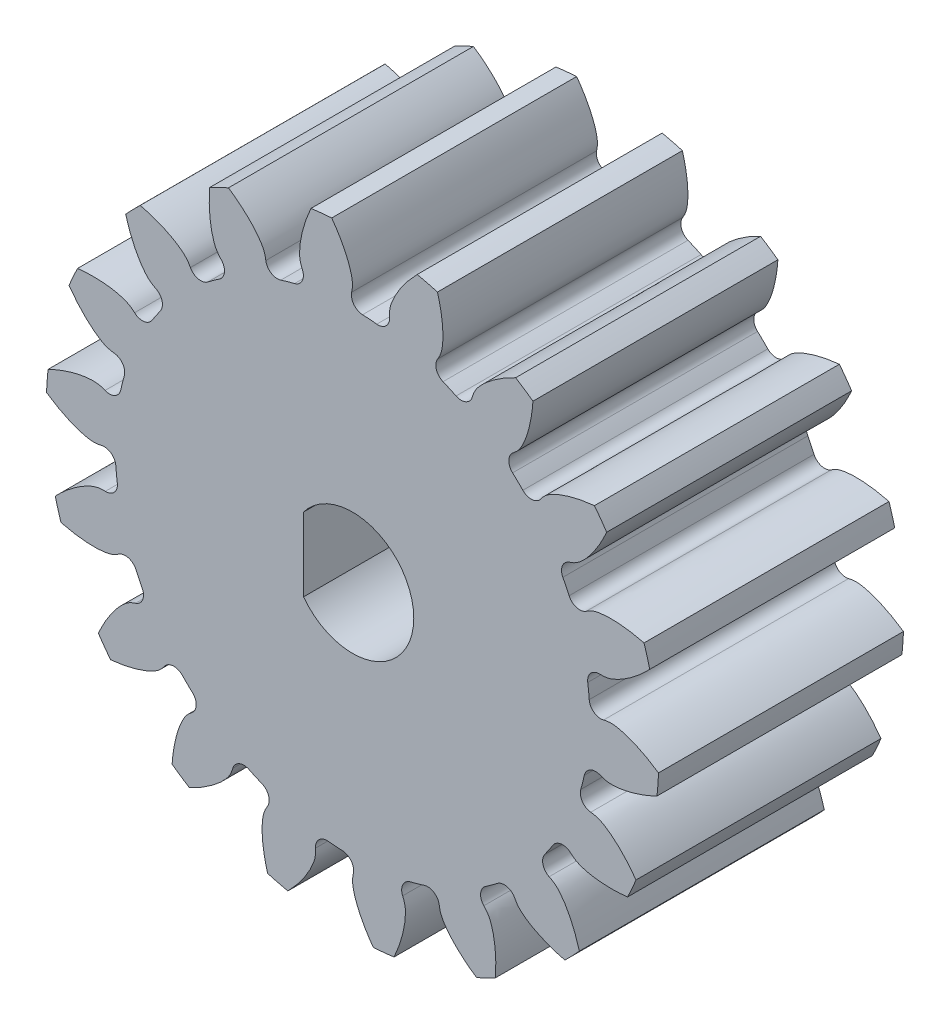
SolidWorks part; units mm, degrees
ref_plane "前视基准面" through (0, 0, 0) normal (0, 0, 1) x (1, 0, 0)
ref_plane "上视基准面" through (0, 0, 0) normal (0, 1, 0) x (1, 0, 0)
ref_plane "右视基准面" through (0, 0, 0) normal (1, 0, 0) x (0, 0, -1)
sketch "草图1" plane through (0, 0, 0) normal (0, 0, 1) x (1, 0, 0)
  line L0 (-0.8, -0.6) -> (-0.8, 0.6)
  arc A0 (-0.8, 0.6) -> (-0.8, -0.6) centre (0, 0) cw
  arc A1 (4.15, 2.7888) -> (3.9504, 3.065) centre (0, 0) ccw
  arc A2 (3.0713, 2.7184) -> (2.7814, 2.698) centre (2.9178, 2.8303) cw
  arc A3 (2.7814, 2.698) -> (2.614, 2.8606) centre (0, 0) ccw
  arc A4 (2.614, 2.8606) -> (2.6257, 3.151) centre (2.7421, 3.0008) cw
  arc A5 (2.9459, 4.04) -> (2.6639, 4.2313) centre (0, 0) ccw
  arc A6 (1.9563, 3.6049) -> (1.6909, 3.4866) centre (1.7738, 3.6576) cw
  arc A7 (1.6909, 3.4866) -> (1.4779, 3.5821) centre (0, 0) ccw
  arc A8 (1.4779, 3.5821) -> (1.3896, 3.859) centre (1.5504, 3.7577) cw
  arc A9 (1.3865, 4.8039) -> (1.0561, 4.8872) centre (0, 0) ccw
  arc A10 (0.6054, 4.0566) -> (0.3964, 3.8547) centre (0.4159, 4.0437) cw
  arc A11 (0.3964, 3.8547) -> (0.1637, 3.8715) centre (0, 0) ccw
  arc A12 (0.1637, 3.8715) -> (-0.014, 4.1015) centre (0.1717, 4.0614) cw
  arc A13 (-0.3402, 4.9884) -> (-0.6792, 4.9537) centre (0, 0) ccw
  arc A14 (-0.8185, 4.019) -> (-0.9459, 3.7578) centre (-0.9922, 3.942) cw
  arc A15 (-0.9459, 3.7578) -> (-1.1703, 3.694) centre (0, 0) ccw
  arc A16 (-1.1703, 3.694) -> (-1.416, 3.8494) centre (-1.2277, 3.8752) cw
  arc A17 (-2.0258, 4.5712) -> (-2.3324, 4.4226) centre (0, 0) ccw
  arc A18 (-2.1438, 3.4967) -> (-2.1741, 3.2077) centre (-2.2807, 3.3649) cw
  arc A19 (-2.1741, 3.2077) -> (-2.3632, 3.071) centre (0, 0) ccw
  arc A20 (-2.3632, 3.071) -> (-2.6471, 3.1329) centre (-2.4791, 3.2216) cw
  arc A21 (-3.4671, 3.6027) -> (-3.7044, 3.3582) centre (0, 0) ccw
  arc A22 (-3.2104, 2.5526) -> (-3.14, 2.2706) centre (-3.294, 2.382) cw
  arc A23 (-3.14, 2.2706) -> (-3.271, 2.0775) centre (0, 0) ccw
  arc A24 (-3.271, 2.0775) -> (-3.559, 2.0386) centre (-3.4314, 2.1794) cw
  arc A25 (-4.4902, 2.1996) -> (-4.6296, 1.8887) centre (0, 0) ccw
  arc A26 (-3.8899, 1.3006) -> (-3.7273, 1.0597) centre (-3.91, 1.1117) cw
  arc A27 (-3.7273, 1.0597) -> (-3.7843, 0.8335) centre (0, 0) ccw
  arc A28 (-3.7843, 0.8335) -> (-4.0416, 0.6984) centre (-3.9699, 0.8743) cw
  arc A29 (-4.9717, 0.5312) -> (-4.9963, 0.1914) centre (0, 0) ccw
  arc A30 (-4.1001, -0.1082) -> (-3.8649, -0.279) centre (-4.0545, -0.2926) cw
  arc A31 (-3.8649, -0.279) -> (-3.8411, -0.5111) centre (0, 0) ccw
  arc A32 (-3.8411, -0.5111) -> (-4.0368, -0.726) centre (-4.0295, -0.5362) cw
  arc A33 (-4.8536, -1.2012) -> (-4.7605, -1.529) centre (0, 0) ccw
  arc A34 (-3.8158, -1.504) -> (-3.5364, -1.584) centre (-3.7098, -1.6617) cw
  arc A35 (-3.5364, -1.584) -> (-3.4347, -1.794) centre (0, 0) ccw
  arc A36 (-3.4347, -1.794) -> (-3.545, -2.0629) centre (-3.6031, -1.882) cw
  arc A37 (-4.15, -2.7888) -> (-3.9504, -3.065) centre (0, 0) ccw
  arc A38 (-3.0713, -2.7184) -> (-2.7814, -2.698) centre (-2.9178, -2.8303) cw
  arc A39 (-2.7814, -2.698) -> (-2.614, -2.8606) centre (0, 0) ccw
  arc A40 (-2.614, -2.8606) -> (-2.6257, -3.151) centre (-2.7421, -3.0008) cw
  arc A41 (-2.9459, -4.04) -> (-2.6639, -4.2313) centre (0, 0) ccw
  arc A42 (-1.9563, -3.6049) -> (-1.6909, -3.4866) centre (-1.7738, -3.6576) cw
  arc A43 (-1.6909, -3.4866) -> (-1.4779, -3.5821) centre (0, 0) ccw
  arc A44 (-1.4779, -3.5821) -> (-1.3896, -3.859) centre (-1.5504, -3.7577) cw
  arc A45 (-1.3865, -4.8039) -> (-1.0561, -4.8872) centre (0, 0) ccw
  arc A46 (-0.6054, -4.0566) -> (-0.3964, -3.8547) centre (-0.4159, -4.0437) cw
  arc A47 (-0.3964, -3.8547) -> (-0.1637, -3.8715) centre (0, 0) ccw
  arc A48 (-0.1637, -3.8715) -> (0.014, -4.1015) centre (-0.1717, -4.0614) cw
  arc A49 (0.3402, -4.9884) -> (0.6792, -4.9537) centre (0, 0) ccw
  arc A50 (0.8185, -4.019) -> (0.9459, -3.7578) centre (0.9922, -3.942) cw
  arc A51 (0.9459, -3.7578) -> (1.1703, -3.694) centre (0, 0) ccw
  arc A52 (1.1703, -3.694) -> (1.416, -3.8494) centre (1.2277, -3.8752) cw
  arc A53 (2.0258, -4.5712) -> (2.3324, -4.4226) centre (0, 0) ccw
  arc A54 (2.1438, -3.4967) -> (2.1741, -3.2077) centre (2.2807, -3.3649) cw
  arc A55 (2.1741, -3.2077) -> (2.3632, -3.071) centre (0, 0) ccw
  arc A56 (2.3632, -3.071) -> (2.6471, -3.1329) centre (2.4791, -3.2216) cw
  arc A57 (3.4671, -3.6027) -> (3.7044, -3.3582) centre (0, 0) ccw
  arc A58 (3.2104, -2.5526) -> (3.14, -2.2706) centre (3.294, -2.382) cw
  arc A59 (3.14, -2.2706) -> (3.271, -2.0775) centre (0, 0) ccw
  arc A60 (3.271, -2.0775) -> (3.559, -2.0386) centre (3.4314, -2.1794) cw
  arc A61 (4.4902, -2.1996) -> (4.6296, -1.8887) centre (0, 0) ccw
  arc A62 (3.8899, -1.3006) -> (3.7273, -1.0597) centre (3.91, -1.1117) cw
  arc A63 (3.7273, -1.0597) -> (3.7843, -0.8335) centre (0, 0) ccw
  arc A64 (3.7843, -0.8335) -> (4.0416, -0.6984) centre (3.9699, -0.8743) cw
  arc A65 (4.9717, -0.5312) -> (4.9963, -0.1914) centre (0, 0) ccw
  arc A66 (4.1001, 0.1082) -> (3.8649, 0.279) centre (4.0545, 0.2926) cw
  arc A67 (3.8649, 0.279) -> (3.8411, 0.5111) centre (0, 0) ccw
  arc A68 (3.8411, 0.5111) -> (4.0368, 0.726) centre (4.0295, 0.5362) cw
  arc A69 (4.8536, 1.2012) -> (4.7605, 1.529) centre (0, 0) ccw
  arc A70 (3.8158, 1.504) -> (3.5364, 1.584) centre (3.7098, 1.6617) cw
  arc A71 (3.5364, 1.584) -> (3.4347, 1.794) centre (0, 0) ccw
  arc A72 (3.4347, 1.794) -> (3.545, 2.0629) centre (3.6031, 1.882) cw
  spline S0 degree 3 poles (4.15, 2.7888) (4.1194, 2.7195) (4.0858, 2.6514) (4.0489, 2.5852) (4.012, 2.5189) (3.9718, 2.4544) (3.9277, 2.3927) (3.8749, 2.3186) (3.8166, 2.2476) (3.7503, 2.1853) (3.706, 2.1437) (3.6558, 2.1059) (3.5996, 2.0827) (3.5817, 2.0753) (3.5635, 2.0688) (3.545, 2.0629) knots 0 0 0 0 0.000227 0.000227 0.000227 0.000455 0.000455 0.000455 0.000728 0.000728 0.000728 0.000912 0.000912 0.000912 0.00097 0.00097 0.00097 0.00097
  spline S1 degree 3 poles (3.0713, 2.7184) (3.1059, 2.7659) (3.1474, 2.8104) (3.1968, 2.8423) (3.3114, 2.9164) (3.4434, 2.9634) (3.5753, 2.9987) (3.698, 3.0314) (3.8241, 3.0527) (3.9504, 3.065) knots 0 0 0 0 0.000176 0.000176 0.000176 0.000584 0.000584 0.000584 0.000961 0.000961 0.000961 0.000961
  spline S2 degree 3 poles (2.9459, 4.04) (2.9408, 3.9644) (2.9325, 3.8889) (2.9205, 3.8141) (2.9085, 3.7392) (2.8928, 3.6648) (2.8725, 3.5917) (2.8482, 3.5041) (2.8177, 3.4174) (2.7767, 3.3362) (2.7493, 3.2819) (2.7151, 3.2292) (2.6702, 3.1882) (2.6559, 3.1752) (2.641, 3.1628) (2.6257, 3.151) knots 0 0 0 0 0.000227 0.000227 0.000227 0.000455 0.000455 0.000455 0.000728 0.000728 0.000728 0.000912 0.000912 0.000912 0.00097 0.00097 0.00097 0.00097
  spline S3 degree 3 poles (1.9563, 3.6049) (1.9726, 3.6614) (1.9964, 3.7174) (2.0319, 3.7642) (2.1142, 3.8731) (2.2222, 3.9624) (2.3341, 4.0407) (2.4382, 4.1134) (2.5494, 4.1765) (2.6639, 4.2313) knots 0 0 0 0 0.000176 0.000176 0.000176 0.000584 0.000584 0.000584 0.000961 0.000961 0.000961 0.000961
  spline S4 degree 3 poles (1.3865, 4.8039) (1.4076, 4.7311) (1.4256, 4.6573) (1.4399, 4.5829) (1.4542, 4.5085) (1.4649, 4.4332) (1.4708, 4.3576) (1.478, 4.2669) (1.479, 4.175) (1.4682, 4.0847) (1.461, 4.0243) (1.4469, 3.9631) (1.4188, 3.9092) (1.4098, 3.8921) (1.4, 3.8754) (1.3896, 3.859) knots 0 0 0 0 0.000227 0.000227 0.000227 0.000455 0.000455 0.000455 0.000728 0.000728 0.000728 0.000912 0.000912 0.000912 0.00097 0.00097 0.00097 0.00097
  spline S5 degree 3 poles (0.6054, 4.0566) (0.6014, 4.1153) (0.6046, 4.176) (0.6219, 4.2322) (0.6621, 4.3627) (0.733, 4.4835) (0.8114, 4.5953) (0.8843, 4.6992) (0.9672, 4.7965) (1.0561, 4.8872) knots 0 0 0 0 0.000176 0.000176 0.000176 0.000584 0.000584 0.000584 0.000961 0.000961 0.000961 0.000961
  spline S6 degree 3 poles (-0.3402, 4.9884) (-0.2955, 4.9272) (-0.2533, 4.8641) (-0.2144, 4.799) (-0.1755, 4.7339) (-0.1397, 4.6668) (-0.1082, 4.5978) (-0.0705, 4.515) (-0.0382, 4.4291) (-0.0174, 4.3405) (-0.0035, 4.2813) (0.0041, 4.219) (-0.0038, 4.1587) (-0.0064, 4.1395) (-0.0099, 4.1205) (-0.014, 4.1015) knots 0 0 0 0 0.000227 0.000227 0.000227 0.000455 0.000455 0.000455 0.000728 0.000728 0.000728 0.000912 0.000912 0.000912 0.00097 0.00097 0.00097 0.00097
  spline S7 degree 3 poles (-0.8185, 4.019) (-0.8424, 4.0728) (-0.8601, 4.1309) (-0.8631, 4.1896) (-0.87, 4.326) (-0.8447, 4.4638) (-0.8093, 4.5957) (-0.7763, 4.7183) (-0.7317, 4.8381) (-0.6792, 4.9537) knots 0 0 0 0 0.000176 0.000176 0.000176 0.000584 0.000584 0.000584 0.000961 0.000961 0.000961 0.000961
  spline S8 degree 3 poles (-2.0258, 4.5712) (-1.9628, 4.529) (-1.9016, 4.4841) (-1.8428, 4.4363) (-1.784, 4.3884) (-1.7274, 4.3376) (-1.6743, 4.2835) (-1.6105, 4.2186) (-1.5507, 4.1489) (-1.5009, 4.0728) (-1.4676, 4.022) (-1.4391, 3.9659) (-1.426, 3.9066) (-1.4218, 3.8877) (-1.4186, 3.8686) (-1.416, 3.8494) knots 0 0 0 0 0.000227 0.000227 0.000227 0.000455 0.000455 0.000455 0.000728 0.000728 0.000728 0.000912 0.000912 0.000912 0.00097 0.00097 0.00097 0.00097
  spline S9 degree 3 poles (-2.1438, 3.4967) (-2.1845, 3.539) (-2.2211, 3.5876) (-2.244, 3.6418) (-2.2971, 3.7675) (-2.3205, 3.9057) (-2.3323, 4.0417) (-2.3432, 4.1682) (-2.3423, 4.296) (-2.3324, 4.4226) knots 0 0 0 0 0.000176 0.000176 0.000176 0.000584 0.000584 0.000584 0.000961 0.000961 0.000961 0.000961
  spline S10 degree 3 poles (-3.4671, 3.6027) (-3.3935, 3.5845) (-3.3206, 3.5633) (-3.249, 3.5385) (-3.1773, 3.5136) (-3.1068, 3.4852) (-3.0383, 3.4526) (-2.9562, 3.4134) (-2.8762, 3.3683) (-2.8033, 3.3138) (-2.7547, 3.2775) (-2.7087, 3.2346) (-2.6761, 3.1833) (-2.6657, 3.167) (-2.6562, 3.1501) (-2.6471, 3.1329) knots 0 0 0 0 0.000227 0.000227 0.000227 0.000455 0.000455 0.000455 0.000728 0.000728 0.000728 0.000912 0.000912 0.000912 0.00097 0.00097 0.00097 0.00097
  spline S11 degree 3 poles (-3.2104, 2.5526) (-3.2632, 2.5785) (-3.3142, 2.6116) (-3.3542, 2.6547) (-3.4471, 2.7547) (-3.5164, 2.8765) (-3.574, 3.0003) (-3.6275, 3.1154) (-3.6704, 3.2359) (-3.7044, 3.3582) knots 0 0 0 0 0.000176 0.000176 0.000176 0.000584 0.000584 0.000584 0.000961 0.000961 0.000961 0.000961
  spline S12 degree 3 poles (-4.4902, 2.1996) (-4.4148, 2.2077) (-4.339, 2.2127) (-4.2633, 2.2138) (-4.1874, 2.215) (-4.1114, 2.2125) (-4.036, 2.2052) (-3.9454, 2.1964) (-3.8548, 2.1815) (-3.7677, 2.1552) (-3.7095, 2.1377) (-3.6516, 2.1131) (-3.6035, 2.076) (-3.5881, 2.0642) (-3.5734, 2.0516) (-3.559, 2.0386) knots 0 0 0 0 0.000227 0.000227 0.000227 0.000455 0.000455 0.000455 0.000728 0.000728 0.000728 0.000912 0.000912 0.000912 0.00097 0.00097 0.00097 0.00097
  spline S13 degree 3 poles (-3.8899, 1.3006) (-3.9483, 1.3069) (-4.0076, 1.3206) (-4.0599, 1.3473) (-4.1814, 1.4096) (-4.2881, 1.5004) (-4.3846, 1.597) (-4.4743, 1.6869) (-4.5557, 1.7854) (-4.6296, 1.8887) knots 0 0 0 0 0.000176 0.000176 0.000176 0.000584 0.000584 0.000584 0.000961 0.000961 0.000961 0.000961
  spline S14 degree 3 poles (-4.9717, 0.5312) (-4.9037, 0.5646) (-4.8341, 0.5952) (-4.7633, 0.6222) (-4.6925, 0.6492) (-4.6202, 0.6728) (-4.5468, 0.6918) (-4.4587, 0.7146) (-4.3684, 0.7315) (-4.2776, 0.7366) (-4.2169, 0.74) (-4.1541, 0.7367) (-4.0962, 0.7184) (-4.0778, 0.7125) (-4.0596, 0.7057) (-4.0416, 0.6984) knots 0 0 0 0 0.000227 0.000227 0.000227 0.000455 0.000455 0.000455 0.000728 0.000728 0.000728 0.000912 0.000912 0.000912 0.00097 0.00097 0.00097 0.00097
  spline S15 degree 3 poles (-4.1001, -0.1082) (-4.1572, -0.1223) (-4.2175, -0.1297) (-4.2759, -0.1225) (-4.4113, -0.1056) (-4.5427, -0.0567) (-4.6664, 0.0011) (-4.7814, 0.0548) (-4.8916, 0.1196) (-4.9963, 0.1914) knots 0 0 0 0 0.000176 0.000176 0.000176 0.000584 0.000584 0.000584 0.000961 0.000961 0.000961 0.000961
  spline S16 degree 3 poles (-4.8536, -1.2012) (-4.8011, -1.1466) (-4.7462, -1.0941) (-4.6889, -1.0445) (-4.6315, -0.9948) (-4.5717, -0.9479) (-4.5092, -0.905) (-4.4342, -0.8535) (-4.3551, -0.8067) (-4.2715, -0.7708) (-4.2157, -0.7469) (-4.1556, -0.7285) (-4.0949, -0.7259) (-4.0755, -0.7251) (-4.0561, -0.7253) (-4.0368, -0.726) knots 0 0 0 0 0.000227 0.000227 0.000227 0.000455 0.000455 0.000455 0.000728 0.000728 0.000728 0.000912 0.000912 0.000912 0.00097 0.00097 0.00097 0.00097
  spline S17 degree 3 poles (-3.8158, -1.504) (-3.8646, -1.5368) (-3.9188, -1.5644) (-3.9761, -1.5775) (-4.1092, -1.608) (-4.2493, -1.607) (-4.3853, -1.595) (-4.5118, -1.5838) (-4.6375, -1.5607) (-4.7605, -1.529) knots 0 0 0 0 0.000176 0.000176 0.000176 0.000584 0.000584 0.000584 0.000961 0.000961 0.000961 0.000961
  spline S18 degree 3 poles (-4.15, -2.7888) (-4.1194, -2.7195) (-4.0858, -2.6514) (-4.0489, -2.5852) (-4.012, -2.5189) (-3.9718, -2.4544) (-3.9277, -2.3927) (-3.8749, -2.3186) (-3.8166, -2.2476) (-3.7503, -2.1853) (-3.706, -2.1437) (-3.6558, -2.1059) (-3.5996, -2.0827) (-3.5817, -2.0753) (-3.5635, -2.0688) (-3.545, -2.0629) knots 0 0 0 0 0.000227 0.000227 0.000227 0.000455 0.000455 0.000455 0.000728 0.000728 0.000728 0.000912 0.000912 0.000912 0.00097 0.00097 0.00097 0.00097
  spline S19 degree 3 poles (-3.0713, -2.7184) (-3.1059, -2.7659) (-3.1474, -2.8104) (-3.1968, -2.8423) (-3.3114, -2.9164) (-3.4434, -2.9634) (-3.5753, -2.9987) (-3.698, -3.0314) (-3.8241, -3.0527) (-3.9504, -3.065) knots 0 0 0 0 0.000176 0.000176 0.000176 0.000584 0.000584 0.000584 0.000961 0.000961 0.000961 0.000961
  spline S20 degree 3 poles (-2.9459, -4.04) (-2.9408, -3.9644) (-2.9325, -3.8889) (-2.9205, -3.8141) (-2.9085, -3.7392) (-2.8928, -3.6648) (-2.8725, -3.5917) (-2.8482, -3.5041) (-2.8177, -3.4174) (-2.7767, -3.3362) (-2.7493, -3.2819) (-2.7151, -3.2292) (-2.6702, -3.1882) (-2.6559, -3.1752) (-2.641, -3.1628) (-2.6257, -3.151) knots 0 0 0 0 0.000227 0.000227 0.000227 0.000455 0.000455 0.000455 0.000728 0.000728 0.000728 0.000912 0.000912 0.000912 0.00097 0.00097 0.00097 0.00097
  spline S21 degree 3 poles (-1.9563, -3.6049) (-1.9726, -3.6614) (-1.9964, -3.7174) (-2.0319, -3.7642) (-2.1142, -3.8731) (-2.2222, -3.9624) (-2.3341, -4.0407) (-2.4382, -4.1134) (-2.5494, -4.1765) (-2.6639, -4.2313) knots 0 0 0 0 0.000176 0.000176 0.000176 0.000584 0.000584 0.000584 0.000961 0.000961 0.000961 0.000961
  spline S22 degree 3 poles (-1.3865, -4.8039) (-1.4076, -4.7311) (-1.4256, -4.6573) (-1.4399, -4.5829) (-1.4542, -4.5085) (-1.4649, -4.4332) (-1.4708, -4.3576) (-1.478, -4.2669) (-1.479, -4.175) (-1.4682, -4.0847) (-1.461, -4.0243) (-1.4469, -3.9631) (-1.4188, -3.9092) (-1.4098, -3.8921) (-1.4, -3.8754) (-1.3896, -3.859) knots 0 0 0 0 0.000227 0.000227 0.000227 0.000455 0.000455 0.000455 0.000728 0.000728 0.000728 0.000912 0.000912 0.000912 0.00097 0.00097 0.00097 0.00097
  spline S23 degree 3 poles (-0.6054, -4.0566) (-0.6014, -4.1153) (-0.6046, -4.176) (-0.6219, -4.2322) (-0.6621, -4.3627) (-0.733, -4.4835) (-0.8114, -4.5953) (-0.8843, -4.6992) (-0.9672, -4.7965) (-1.0561, -4.8872) knots 0 0 0 0 0.000176 0.000176 0.000176 0.000584 0.000584 0.000584 0.000961 0.000961 0.000961 0.000961
  spline S24 degree 3 poles (0.3402, -4.9884) (0.2955, -4.9272) (0.2533, -4.8641) (0.2144, -4.799) (0.1755, -4.7339) (0.1397, -4.6668) (0.1082, -4.5978) (0.0705, -4.515) (0.0382, -4.4291) (0.0174, -4.3405) (0.0035, -4.2813) (-0.0041, -4.219) (0.0038, -4.1587) (0.0064, -4.1395) (0.0099, -4.1205) (0.014, -4.1015) knots 0 0 0 0 0.000227 0.000227 0.000227 0.000455 0.000455 0.000455 0.000728 0.000728 0.000728 0.000912 0.000912 0.000912 0.00097 0.00097 0.00097 0.00097
  spline S25 degree 3 poles (0.8185, -4.019) (0.8424, -4.0728) (0.8601, -4.1309) (0.8631, -4.1896) (0.87, -4.326) (0.8447, -4.4638) (0.8093, -4.5957) (0.7763, -4.7183) (0.7317, -4.8381) (0.6792, -4.9537) knots 0 0 0 0 0.000176 0.000176 0.000176 0.000584 0.000584 0.000584 0.000961 0.000961 0.000961 0.000961
  spline S26 degree 3 poles (2.0258, -4.5712) (1.9628, -4.529) (1.9016, -4.4841) (1.8428, -4.4363) (1.784, -4.3884) (1.7274, -4.3376) (1.6743, -4.2835) (1.6105, -4.2186) (1.5507, -4.1489) (1.5009, -4.0728) (1.4676, -4.022) (1.4391, -3.9659) (1.426, -3.9066) (1.4218, -3.8877) (1.4186, -3.8686) (1.416, -3.8494) knots 0 0 0 0 0.000227 0.000227 0.000227 0.000455 0.000455 0.000455 0.000728 0.000728 0.000728 0.000912 0.000912 0.000912 0.00097 0.00097 0.00097 0.00097
  spline S27 degree 3 poles (2.1438, -3.4967) (2.1845, -3.539) (2.2211, -3.5876) (2.244, -3.6418) (2.2971, -3.7675) (2.3205, -3.9057) (2.3323, -4.0417) (2.3432, -4.1682) (2.3423, -4.296) (2.3324, -4.4226) knots 0 0 0 0 0.000176 0.000176 0.000176 0.000584 0.000584 0.000584 0.000961 0.000961 0.000961 0.000961
  spline S28 degree 3 poles (3.4671, -3.6027) (3.3935, -3.5845) (3.3206, -3.5633) (3.249, -3.5385) (3.1773, -3.5136) (3.1068, -3.4852) (3.0383, -3.4526) (2.9562, -3.4134) (2.8762, -3.3683) (2.8033, -3.3138) (2.7547, -3.2775) (2.7087, -3.2346) (2.6761, -3.1833) (2.6657, -3.167) (2.6562, -3.1501) (2.6471, -3.1329) knots 0 0 0 0 0.000227 0.000227 0.000227 0.000455 0.000455 0.000455 0.000728 0.000728 0.000728 0.000912 0.000912 0.000912 0.00097 0.00097 0.00097 0.00097
  spline S29 degree 3 poles (3.2104, -2.5526) (3.2632, -2.5785) (3.3142, -2.6116) (3.3542, -2.6547) (3.4471, -2.7547) (3.5164, -2.8765) (3.574, -3.0003) (3.6275, -3.1154) (3.6704, -3.2359) (3.7044, -3.3582) knots 0 0 0 0 0.000176 0.000176 0.000176 0.000584 0.000584 0.000584 0.000961 0.000961 0.000961 0.000961
  spline S30 degree 3 poles (4.4902, -2.1996) (4.4148, -2.2077) (4.339, -2.2127) (4.2633, -2.2138) (4.1874, -2.215) (4.1114, -2.2125) (4.036, -2.2052) (3.9454, -2.1964) (3.8548, -2.1815) (3.7677, -2.1552) (3.7095, -2.1377) (3.6516, -2.1131) (3.6035, -2.076) (3.5881, -2.0642) (3.5734, -2.0516) (3.559, -2.0386) knots 0 0 0 0 0.000227 0.000227 0.000227 0.000455 0.000455 0.000455 0.000728 0.000728 0.000728 0.000912 0.000912 0.000912 0.00097 0.00097 0.00097 0.00097
  spline S31 degree 3 poles (3.8899, -1.3006) (3.9483, -1.3069) (4.0076, -1.3206) (4.0599, -1.3473) (4.1814, -1.4096) (4.2881, -1.5004) (4.3846, -1.597) (4.4743, -1.6869) (4.5557, -1.7854) (4.6296, -1.8887) knots 0 0 0 0 0.000176 0.000176 0.000176 0.000584 0.000584 0.000584 0.000961 0.000961 0.000961 0.000961
  spline S32 degree 3 poles (4.9717, -0.5312) (4.9037, -0.5646) (4.8341, -0.5952) (4.7633, -0.6222) (4.6925, -0.6492) (4.6202, -0.6728) (4.5468, -0.6918) (4.4587, -0.7146) (4.3684, -0.7315) (4.2776, -0.7366) (4.2169, -0.74) (4.1541, -0.7367) (4.0962, -0.7184) (4.0778, -0.7125) (4.0596, -0.7057) (4.0416, -0.6984) knots 0 0 0 0 0.000227 0.000227 0.000227 0.000455 0.000455 0.000455 0.000728 0.000728 0.000728 0.000912 0.000912 0.000912 0.00097 0.00097 0.00097 0.00097
  spline S33 degree 3 poles (4.1001, 0.1082) (4.1572, 0.1223) (4.2175, 0.1297) (4.2759, 0.1225) (4.4113, 0.1056) (4.5427, 0.0567) (4.6664, -0.0011) (4.7814, -0.0548) (4.8916, -0.1196) (4.9963, -0.1914) knots 0 0 0 0 0.000176 0.000176 0.000176 0.000584 0.000584 0.000584 0.000961 0.000961 0.000961 0.000961
  spline S34 degree 3 poles (4.8536, 1.2012) (4.8011, 1.1466) (4.7462, 1.0941) (4.6889, 1.0445) (4.6315, 0.9948) (4.5717, 0.9479) (4.5092, 0.905) (4.4342, 0.8535) (4.3551, 0.8067) (4.2715, 0.7708) (4.2157, 0.7469) (4.1556, 0.7285) (4.0949, 0.7259) (4.0755, 0.7251) (4.0561, 0.7253) (4.0368, 0.726) knots 0 0 0 0 0.000227 0.000227 0.000227 0.000455 0.000455 0.000455 0.000728 0.000728 0.000728 0.000912 0.000912 0.000912 0.00097 0.00097 0.00097 0.00097
  spline S35 degree 3 poles (3.8158, 1.504) (3.8646, 1.5368) (3.9188, 1.5644) (3.9761, 1.5775) (4.1092, 1.608) (4.2493, 1.607) (4.3853, 1.595) (4.5118, 1.5838) (4.6375, 1.5607) (4.7605, 1.529) knots 0 0 0 0 0.000176 0.000176 0.000176 0.000584 0.000584 0.000584 0.000961 0.000961 0.000961 0.000961
extrude "凸台-拉伸1" add sketch "草图1" against normal blind 4
sketch "草图2" plane through (0, 0, 0) normal (0, 0, 1) x (1, 0, 0)
  circle A0 centre (0, 0) radius 4.5
